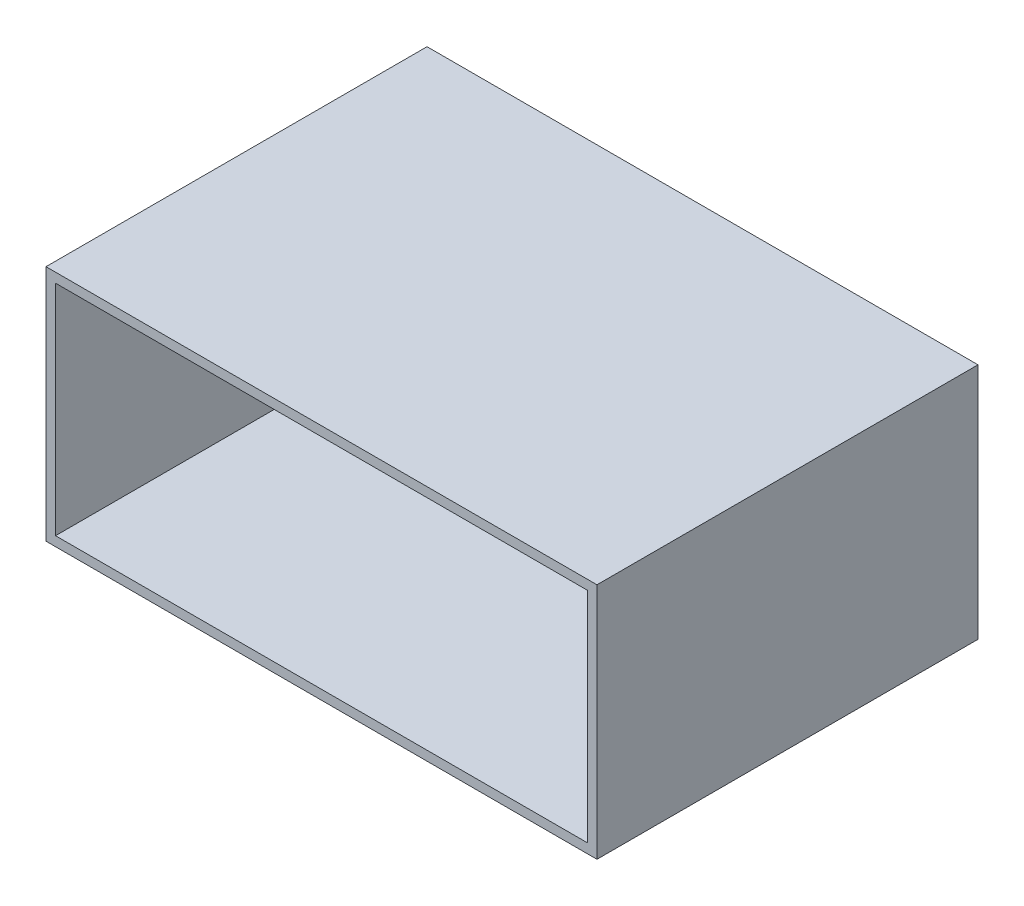
SolidWorks part; units mm, degrees
ref_plane "Front Plane" through (0, 0, 0) normal (0, 0, 1) x (1, 0, 0)
ref_plane "Top Plane" through (0, 0, 0) normal (0, 1, 0) x (1, 0, 0)
ref_plane "Right Plane" through (0, 0, 0) normal (1, 0, 0) x (0, 0, -1)
sketch "Sketch1" plane through (0, 0, 0) normal (0, 0, 1) x (1, 0, 0)
  line L1 (0, 0) -> (177.292, 0)
  line L2 (0, 0) -> (0, 72.898)
  line L3 (0, 72.898) -> (177.292, 72.898)
  line L4 (177.292, 0) -> (177.292, 72.898)
  dimension "D1" = 72.898
  dimension "D2" = 177.292
extrude "Extrude-Thin1" add sketch "Sketch1" along normal blind 127 thin
